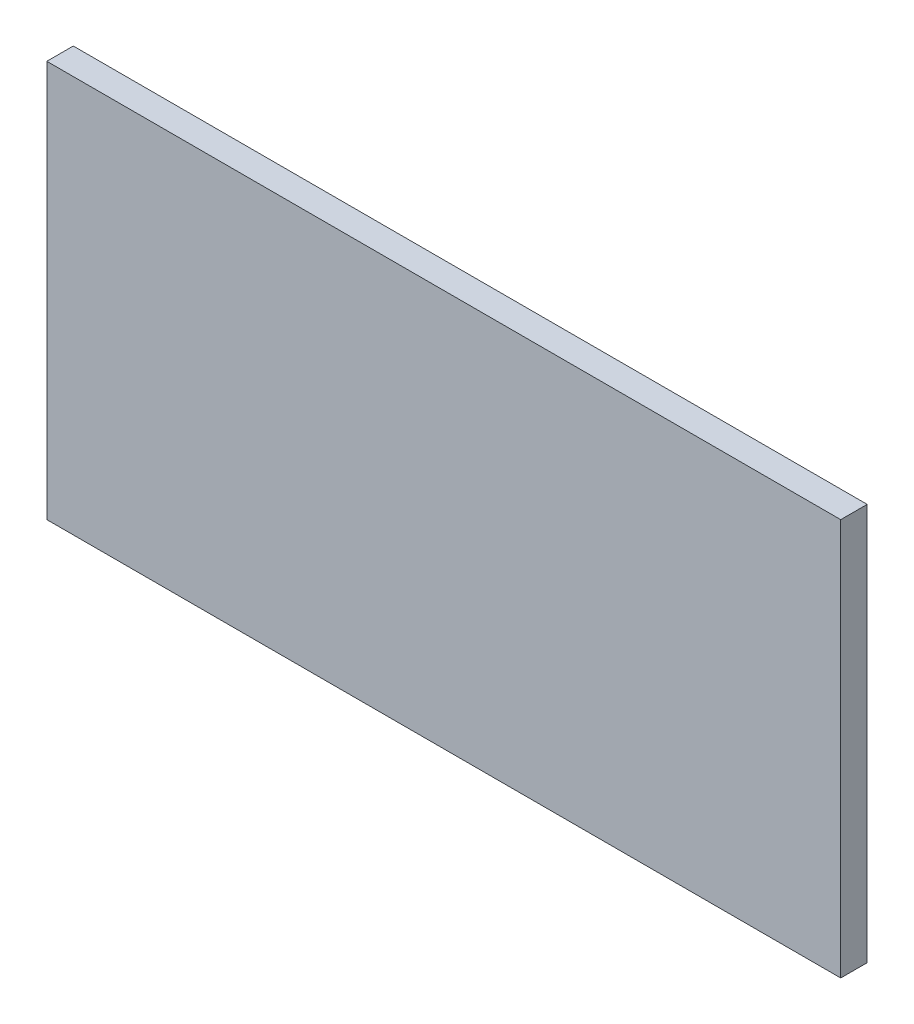
SolidWorks part; units mm, degrees
ref_plane "Front Plane" through (0, 0, 0) normal (0, 0, 1) x (1, 0, 0)
ref_plane "Top Plane" through (0, 0, 0) normal (0, 1, 0) x (1, 0, 0)
ref_plane "Right Plane" through (0, 0, 0) normal (1, 0, 0) x (0, 0, -1)
sketch "Sketch1" plane through (0, 0, 0) normal (0, 0, 1) x (1, 0, 0)
  line L1 (-75, 37.5) -> (75, 37.5)
  line L2 (-75, 37.5) -> (-75, -37.5)
  line L3 (-75, -37.5) -> (75, -37.5)
  line L4 (75, 37.5) -> (75, -37.5)
  line L5 (-75, 37.5) -> (75, -37.5) construction
  line L6 (-75, -37.5) -> (75, 37.5) construction
  point P0 (0, 0)
  dimension "D1" = 75
  dimension "D2" = 150
extrude "Boss-Extrude1" add sketch "Sketch1" along normal blind 5
sketch "Sketch2" plane through (0, 0, 0) normal (0, 0, -1) x (-1, 0, 0)
  line L1 (-3.75, 3.75) -> (3.75, 3.75)
  line L2 (-3.75, 3.75) -> (-3.75, -3.75)
  line L3 (-3.75, -3.75) -> (3.75, -3.75)
  line L4 (3.75, 3.75) -> (3.75, -3.75)
  line L5 (-3.75, 3.75) -> (3.75, -3.75) construction
  line L6 (-3.75, -3.75) -> (3.75, 3.75) construction
  point P0 (0, 0)
  dimension "D1" = 7.5
  dimension "D2" = 7.5
extrude "Boss-Extrude2" add sketch "Sketch2" along normal blind 2
sketch "Sketch3" plane through (0, 0, -2) normal (0, 0, -1) x (-1, 0, 0)
  line L0 (-3.75, -3.75) -> (3.75, -3.75) construction
  line L1 (-2, 3.75) -> (2, 3.75)
  line L2 (-2, 3.75) -> (-2, -3.75)
  line L3 (-2, -3.75) -> (2, -3.75)
  line L4 (2, 3.75) -> (2, -3.75)
  line L5 (-2, 3.75) -> (2, -3.75) construction
  line L6 (-2, -3.75) -> (2, 3.75) construction
  point P0 (0, 0)
  dimension "D1" = 4
extrude "Boss-Extrude3" add sketch "Sketch3" along normal blind 7
fillet "Fillet1" radius 2 2 edges at (0, -3.75, -9) (0, 3.75, -9)
sketch "Sketch6" plane through (2, 0, 0) normal (1, 0, 0) x (0, 0, -1)
  line L0 (6, 0) -> (9, 0) construction
  line L1 (9, 1.75) -> (9, -1.75) construction
  circle A0 centre (6, 0) radius 2
  dimension "D1" = 4
extrude "Cut-Extrude1" cut sketch "Sketch6" against normal blind 5
